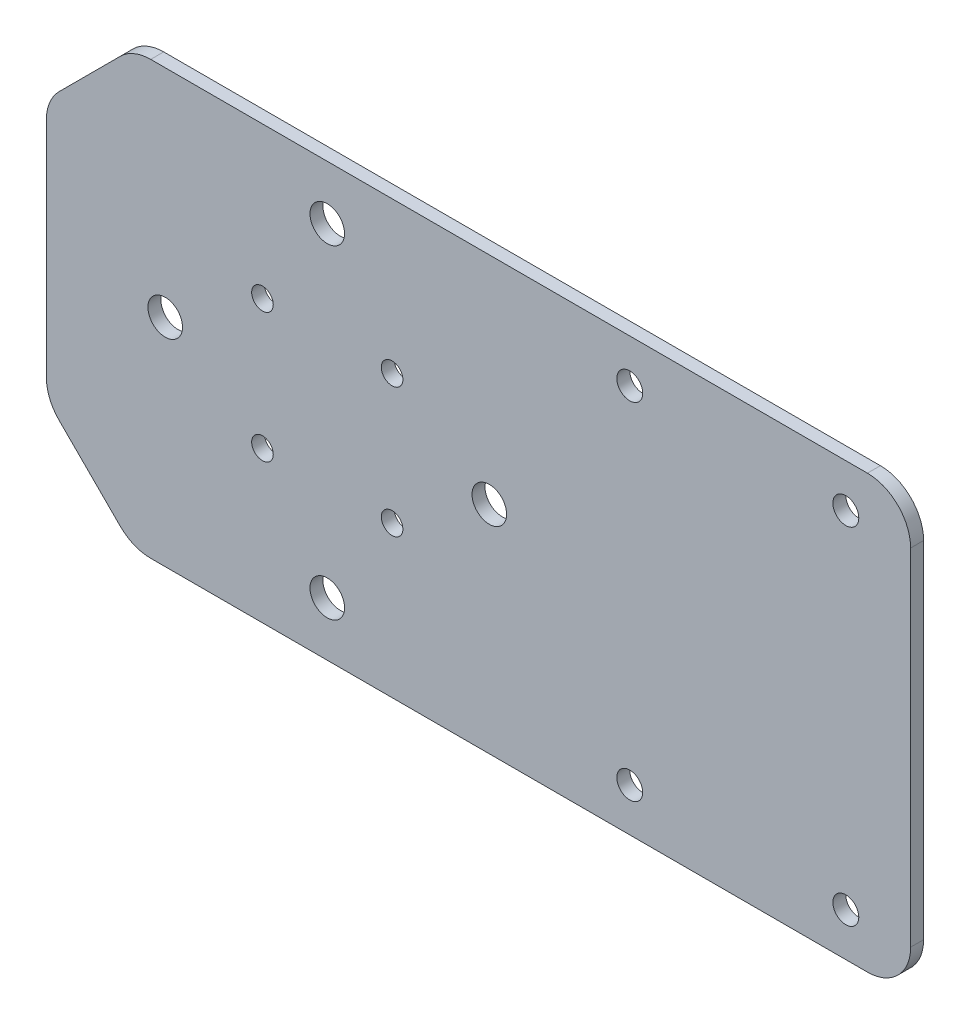
SolidWorks part; units mm, degrees
ref_plane "Front Plane" through (0, 0, 0) normal (0, 0, 1) x (1, 0, 0)
ref_plane "Top Plane" through (0, 0, 0) normal (0, 1, 0) x (1, 0, 0)
ref_plane "Right Plane" through (0, 0, 0) normal (1, 0, 0) x (0, 0, -1)
sketch "Sketch1" plane through (0, 0, 0) normal (0, 0, 1) x (1, 0, 0)
  circle A0 centre (0, 0) radius 60
  circle A1 centre (0, 37.5) radius 4
  circle A2 centre (0, 0) radius 60
  circle A3 centre (37.5, 0) radius 4
  circle A4 centre (0, 0) radius 60
  circle A5 centre (0, -37.5) radius 4
  circle A6 centre (0, 0) radius 60
  circle A7 centre (-37.5, 0) radius 4
  point P17 (0, 0)
  dimension "D2" = 120
  dimension "D4" = 4
extrude "Boss-Extrude1" add sketch "Sketch1" along normal blind 3 contours A0 A7 A5 A3 A1
sketch "Sketch2" plane through (0, 0, 3) normal (0, 0, 1) x (1, 0, 0)
  line L1 (-50, 21) -> (60, 21)
  line L2 (-50, 21) -> (-50, 9)
  line L3 (-50, 9) -> (60, 9)
  line L4 (60, 21) -> (60, 9)
  dimension "D1" = 12
  dimension "D2" = 110
  dimension "D3" = 50
  dimension "D4" = 21
extrude "Boss-Extrude2" add sketch "Sketch2" along normal blind 4
hole_wizard "Ø5.0 (5) Diameter Hole1" positions "Sketch4" profile "Sketch3" hole size "Ø5.0" standard "ISO" end condition through all
sketch "Sketch4" plane through (0, 0, 7) normal (0, 0, 1) x (1, 0, 0)
  line L0 (-50, 9) -> (60, 9) construction
  point P0 (-15, 15)
  point P2 (15, 15)
  point P8 (-15, -15)
  point P10 (15, -15)
  dimension "D1" = 30
  dimension "D2" = 15
  dimension "D3" = 6
  dimension "D4" = 6
  dimension "D5" = 30
  dimension "D6" = 30
  dimension "D7" = 30
  dimension "D8" = 15
sketch "Sketch3" plane through (-15, 15, 7) normal (1, 0, 0) x (0, -1, 0)
  line L0 (0, 0) -> (0, 7)
  line L1 (0, 7) -> (2.5, 7)
  line L2 (2.5, 7) -> (2.5, 0)
  line L5 (2.5, 0) -> (0, 0)
  line L11 (0, -6.35) -> (0, 107.95) construction
  dimension "Thru Hole Dia." = 5
  dimension "Thru Hole Depth" = 7
sketch "Sketch5" plane through (0, 0, 3) normal (0, 0, 1) x (1, 0, 0)
  line L1 (25, -50) -> (135, -50)
  line L2 (25, -50) -> (25, 50)
  line L3 (25, 50) -> (135, 50)
  line L4 (135, -50) -> (135, 50)
  circle A0 centre (70, 39.998) radius 3
  circle A1 centre (120, 40) radius 3
  circle A2 centre (120, -40) radius 3
  circle A3 centre (70, -40.002) radius 3
  dimension "D3" = 80
  dimension "D4" = 80
  dimension "D5" = 100
  dimension "D6" = 10
  dimension "D7" = 6
  dimension "D8" = 6
  dimension "D9" = 6
  dimension "D10" = 6
  dimension "D13" = 70
  dimension "D16" = 10.002
  dimension "D1" = 50
  dimension "D2" = 50
  dimension "D11" = 110
  dimension "D12" = 50
  dimension "D14" = 45
  dimension "D15" = 25
extrude "Boss-Extrude3" add sketch "Sketch5" against normal blind 3
sketch "Sketch6" plane through (0, 0, 3) normal (0, 0, 1) x (1, 0, 0)
  line L0 (-20, 50) -> (-46.2315, 0)
  line L1 (135, 50) -> (-65, 50)
  line L2 (135, 50) -> (135, -50)
  line L3 (135, -50) -> (-65, -50)
  line L4 (-65, 50) -> (-65, -50)
  line L5 (-46.2315, 0) -> (-20, -50)
  arc M4 (33.1662, 50) -> (33.1662, -50) centre (0, 0) ccw
  line M5 (-50, 21) -> (60, 21)
  line M7 (60, 9) -> (-50, 9)
  arc M8 (33.1662, 50) -> (33.1662, -50) centre (0, 0) ccw
  dimension "D1" = 200
  dimension "D2" = 100
  dimension "D3" = 45
  dimension "D4" = 45
  dimension "D5" = 18.7685
  dimension "D6" = 50
extrude "Boss-Extrude4" add sketch "Sketch6" against normal blind 3 contours L1 L4 L3 L0 M8 M7 M5 M4
sketch "Sketch7" plane through (0, 0, 3) normal (0, 0, 1) x (1, 0, 0)
  line L1 (-65, 50) -> (135, 50)
  line L2 (-65, 50) -> (-65, -50)
  line L3 (-65, -50) -> (135, -50)
  line L4 (135, 50) -> (135, -50)
  line L5 (160, 75) -> (-90, 75)
  line L6 (160, 75) -> (160, -75)
  line L7 (160, -75) -> (-90, -75)
  line L8 (-90, 75) -> (-90, -75)
  dimension "D1" = 25
  dimension "D2" = 25
  dimension "D3" = 25
  dimension "D4" = 25
extrude "Cut-Extrude1" cut sketch "Sketch7" against normal blind 5
chamfer "Chamfer1" distance 20 angle 45 2 edges at (-65, 50, 1.5) (-65, -50, 1.5)
sketch "Sketch8" plane through (0, 0, 3) normal (0, 0, 1) x (1, 0, 0)
  circle A0 centre (37.5, 0) radius 4
  dimension "D1" = 8
  dimension "D2" = 37.5
extrude "Cut-Extrude2" cut sketch "Sketch8" against normal blind 15
fillet "Fillet1" radius 10 6 edges at (-45, -50, 1.5) (-65, -30, 1.5) (-65, 30, 1.5) (-45, 50, 1.5) (135, -50, 1.5) (135, 50, 1.5)
sketch "Sketch9" plane through (0, 0, 7) normal (0, 0, 1) x (1, 0, 0)
  line L1 (-50, 21) -> (60, 21)
  line L2 (-50, 21) -> (-50, 9)
  line L3 (-50, 9) -> (60, 9)
  line L4 (60, 21) -> (60, 9)
  circle A0 centre (-15, 15) radius 2.5
  circle A1 centre (15, 15) radius 2.5
extrude "Cut-Extrude3" cut sketch "Sketch9" against normal blind 4
